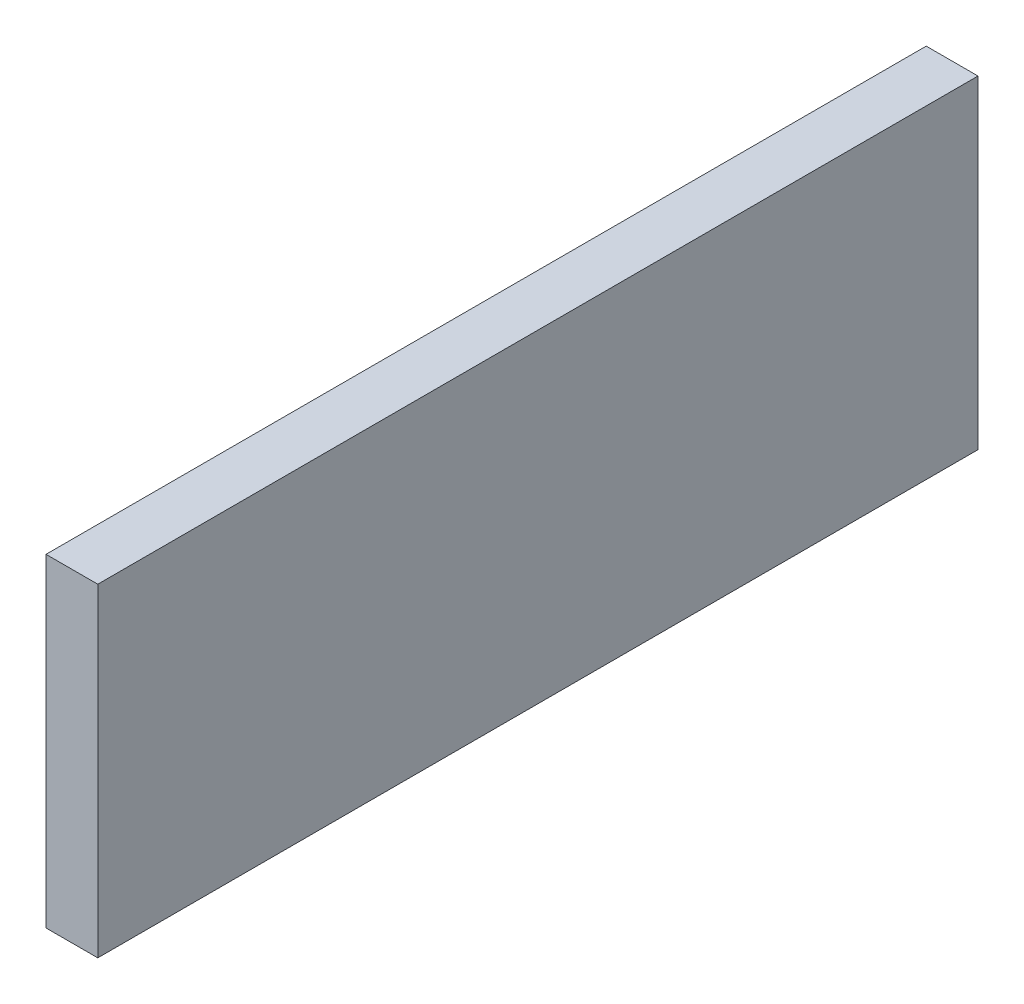
SolidWorks part; units mm, degrees
ref_plane "Front Plane" through (0, 0, 0) normal (0, 0, 1) x (1, 0, 0)
ref_plane "Top Plane" through (0, 0, 0) normal (0, 1, 0) x (1, 0, 0)
ref_plane "Right Plane" through (0, 0, 0) normal (1, 0, 0) x (0, 0, -1)
sketch "Sketch1" plane through (0, 0, 0) normal (1, 0, 0) x (0, 0, -1)
  line L1 (-26.4878, 12.0122) -> (41.5122, 12.0122)
  line L2 (-26.4878, 12.0122) -> (-26.4878, -12.9878)
  line L3 (-26.4878, -12.9878) -> (41.5122, -12.9878)
  line L4 (41.5122, 12.0122) -> (41.5122, -12.9878)
  dimension "D1" = 68
  dimension "D2" = 25
extrude "Boss-Extrude1" add sketch "Sketch1" along normal blind 4
